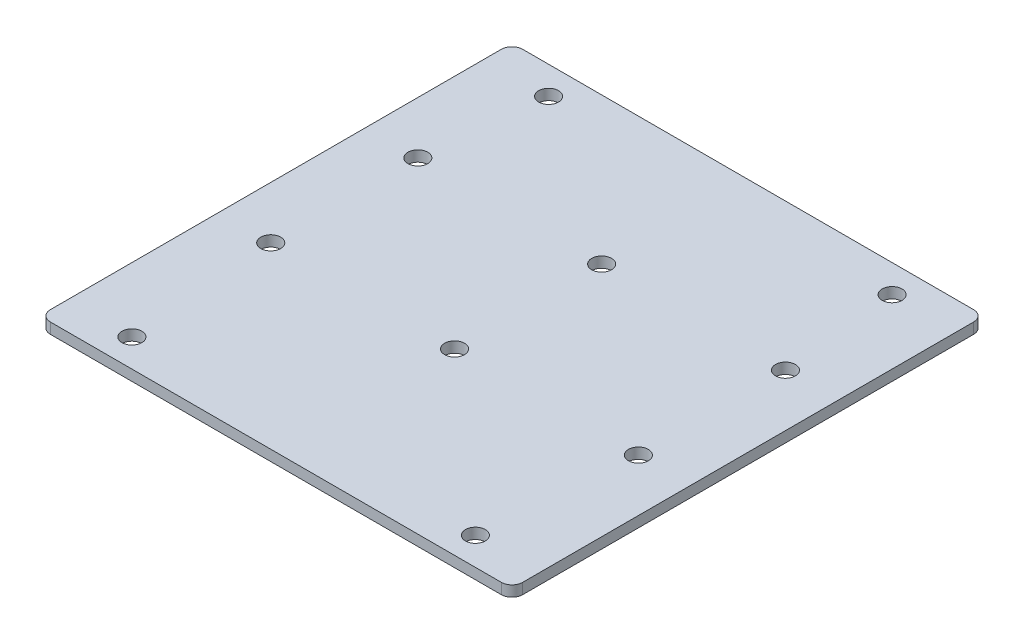
SolidWorks part; units mm, degrees
material "Acrylic (Medium-high impact)"
ref_plane "Front Plane" through (0, 0, 0) normal (0, 0, 1) x (1, 0, 0)
ref_plane "Top Plane" through (0, 0, 0) normal (0, 1, 0) x (1, 0, 0)
ref_plane "Right Plane" through (0, 0, 0) normal (1, 0, 0) x (0, 0, -1)
sketch "Sketch1" plane through (0, 0, 0) normal (0, 1, 0) x (1, 0, 0)
  line L1 (44, -44) -> (-44, -44)
  line L2 (44, -44) -> (44, 44)
  line L3 (44, 44) -> (-44, 44)
  line L4 (-44, -44) -> (-44, 44)
  line L5 (44, -44) -> (-44, 44) construction
  line L6 (44, 44) -> (-44, -44) construction
  point P0 (0, 0)
  dimension "D1" = 88
  dimension "D2" = 88
extrude "Boss-Extrude1" add sketch "Sketch1" along normal blind 2
fillet "Fillet1" radius 2 4 edges at (-44, 1, -44) (44, 1, -44) (-44, 1, 44) (44, 1, 44)
sketch "Sketch2" plane through (0, 0, 0) normal (0, -1, 0) x (1, 0, 0)
  circle A0 centre (-32, 38.82) radius 1.85
  circle A1 centre (32, 38.82) radius 1.85
  circle A2 centre (32, -38.82) radius 1.85
  circle A3 centre (-32, -38.82) radius 1.85
  dimension "D1" = 3.7
extrude "Cut-Extrude1" cut sketch "Sketch2" against normal blind 10
sketch "Sketch3" plane through (0, 0, 0) normal (0, -1, 0) x (1, 0, 0)
  circle A0 centre (-34.25, 10.7) radius 1.85
  circle A1 centre (0, 10.7) radius 1.85
  circle A2 centre (34.25, 10.7) radius 1.85
  circle A3 centre (34.25, -16.7) radius 1.85
  circle A4 centre (0, -16.7) radius 1.85
  circle A5 centre (-34.25, -16.7) radius 1.85
  dimension "D1" = 3.7
extrude "Cut-Extrude2" cut sketch "Sketch3" against normal blind 5
